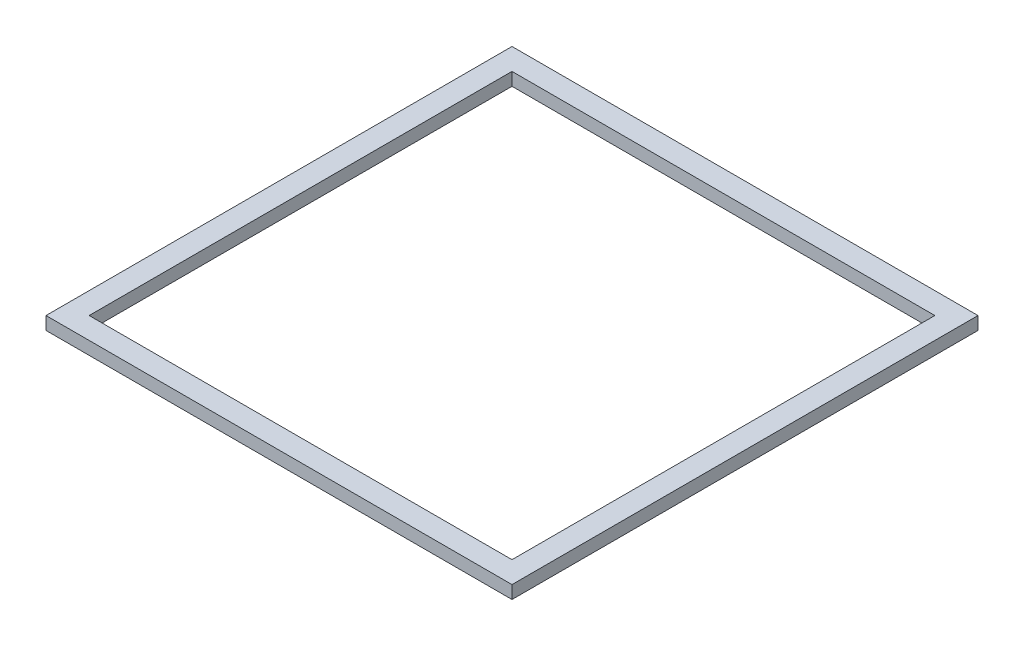
SolidWorks part; units mm, degrees
ref_plane "정면" through (0, 0, 0) normal (0, 0, 1) x (1, 0, 0)
ref_plane "윗면" through (0, 0, 0) normal (0, 1, 0) x (1, 0, 0)
ref_plane "우측면" through (0, 0, 0) normal (1, 0, 0) x (0, 0, -1)
sketch "스케치1" plane through (0, 0, 0) normal (0, 1, 0) x (1, 0, 0)
  line L1 (-54, -54) -> (54, -54)
  line L2 (-54, -54) -> (-54, 54)
  line L3 (-54, 54) -> (54, 54)
  line L4 (54, -54) -> (54, 54)
  line L5 (-54, -54) -> (54, 54) construction
  line L6 (-54, 54) -> (54, -54) construction
  line L7 (-49, -49) -> (49, -49)
  line L8 (-49, -49) -> (-49, 49)
  line L9 (-49, 49) -> (49, 49)
  line L10 (49, -49) -> (49, 49)
  line L11 (-49, -49) -> (49, 49) construction
  line L12 (-49, 49) -> (49, -49) construction
  point P0 (0, 0)
  point P7 (0, 0)
  dimension "D1" = 108
  dimension "D2" = 108
  dimension "D3" = 98
extrude "보스-돌출1" add sketch "스케치1" along normal blind 3
